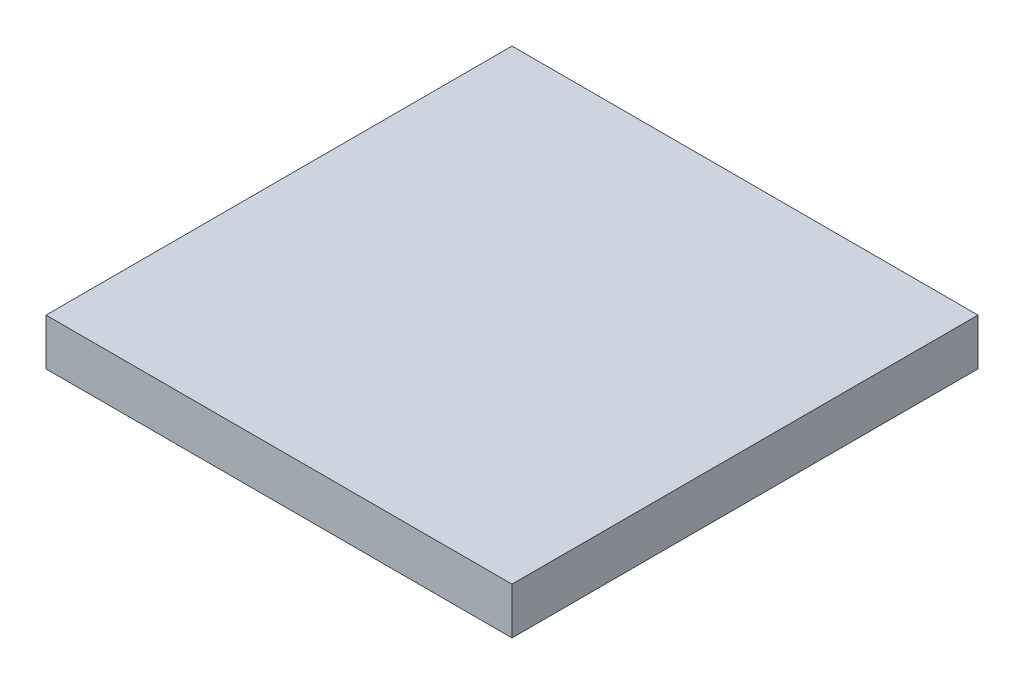
SolidWorks part; units mm, degrees
ref_plane "Front Plane" through (0, 0, 0) normal (0, 0, 1) x (1, 0, 0)
ref_plane "Top Plane" through (0, 0, 0) normal (0, 1, 0) x (1, 0, 0)
ref_plane "Right Plane" through (0, 0, 0) normal (1, 0, 0) x (0, 0, -1)
sketch "Sketch1" plane through (0, 0, 0) normal (0, 1, 0) x (1, 0, 0)
  line L1 (-50, 50) -> (50, 50)
  line L2 (-50, 50) -> (-50, -50)
  line L3 (-50, -50) -> (50, -50)
  line L4 (50, 50) -> (50, -50)
  line L5 (-50, 50) -> (50, -50) construction
  line L6 (-50, -50) -> (50, 50) construction
  point P0 (0, 0)
  dimension "D1" = 100
  dimension "D2" = 100
extrude "Boss-Extrude1" add sketch "Sketch1" along normal blind 10
